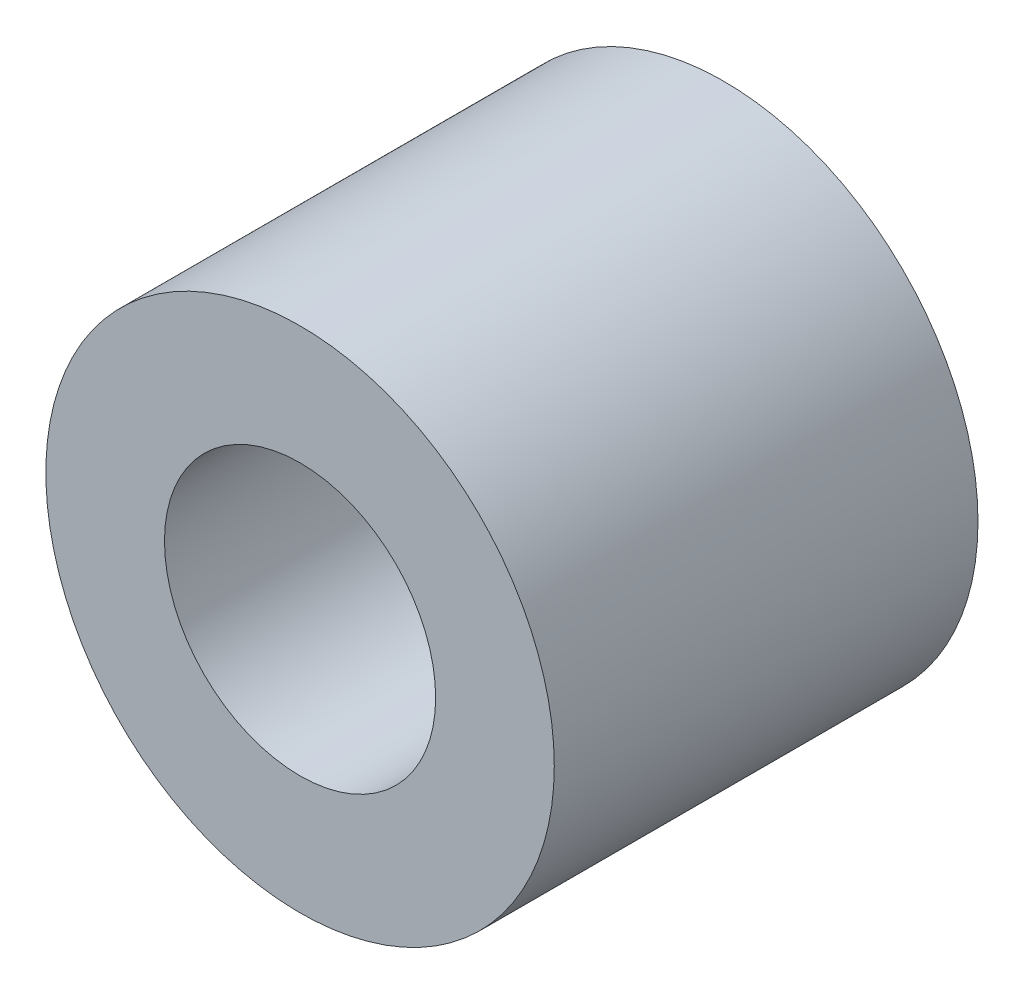
SolidWorks part; units mm, degrees
ref_plane "Front Plane" through (0, 0, 0) normal (0, 0, 1) x (1, 0, 0)
ref_plane "Top Plane" through (0, 0, 0) normal (0, 1, 0) x (1, 0, 0)
ref_plane "Right Plane" through (0, 0, 0) normal (1, 0, 0) x (0, 0, -1)
sketch "Sketch1" plane through (0, 0, 0) normal (0, 0, 1) x (1, 0, 0)
  circle A0 centre (0, 0) radius 1.6
  circle A1 centre (0, 0) radius 3
  dimension "D1" = 3.2
  dimension "D2" = 6
extrude "Boss-Extrude1" add sketch "Sketch1" along normal blind 5
